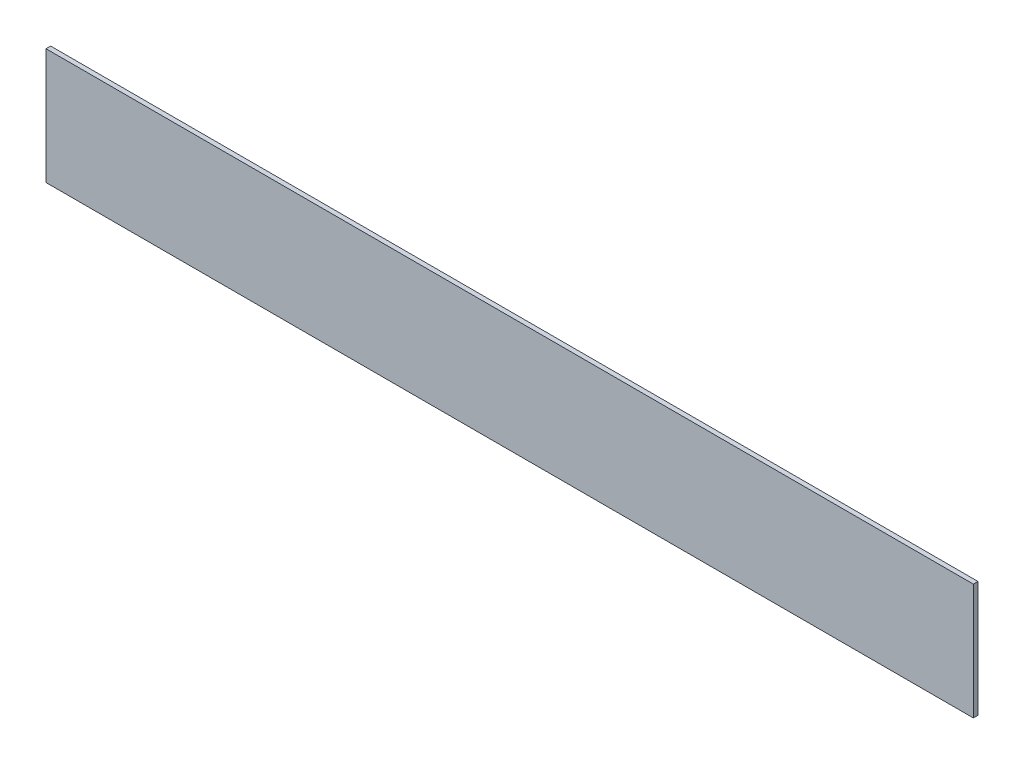
SolidWorks part; units mm, degrees
ref_plane "Front Plane" through (0, 0, 0) normal (0, 0, 1) x (1, 0, 0)
ref_plane "Top Plane" through (0, 0, 0) normal (0, 1, 0) x (1, 0, 0)
ref_plane "Right Plane" through (0, 0, 0) normal (1, 0, 0) x (0, 0, -1)
other "Configuration Table"
sketch "Sketch1" plane through (0, 0, 0) normal (0, 0, 1) x (1, 0, 0)
  line L1 (0, 41.6) -> (320, 41.6)
  line L2 (0, 41.6) -> (0, 81.6)
  line L3 (0, 81.6) -> (320, 81.6)
  line L4 (320, 41.6) -> (320, 81.6)
extrude "KUTU_on_dil_1" add sketch "Sketch1" along normal blind 1.6 separate body
